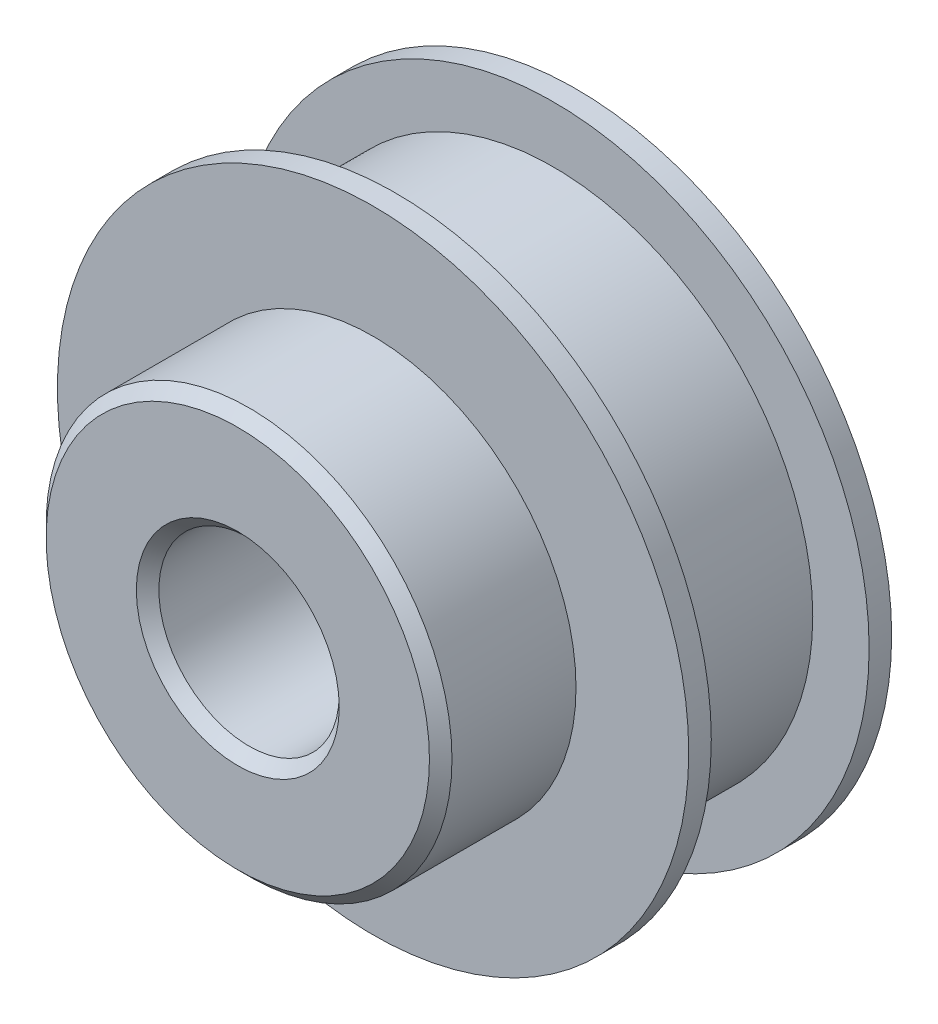
SolidWorks part; units mm, degrees
ref_plane "Front Plane" through (0, 0, 0) normal (0, 0, 1) x (1, 0, 0)
ref_plane "Top Plane" through (0, 0, 0) normal (0, 1, 0) x (1, 0, 0)
ref_plane "Right Plane" through (0, 0, 0) normal (1, 0, 0) x (0, 0, -1)
sketch "Sketch1" plane through (0, 0, 0) normal (0, 0, 1) x (1, 0, 0)
  circle A0 centre (0, 0) radius 14
  dimension "D1" = 28
extrude "Boss-Extrude1" add sketch "Sketch1" along normal blind 1
sketch "Sketch2" plane through (0, 0, 1) normal (0, 0, 1) x (1, 0, 0)
  circle A0 centre (0, 0) radius 11.5
  dimension "D1" = 23
extrude "Boss-Extrude2" add sketch "Sketch2" along normal blind 7
sketch "Sketch3" plane through (0, 0, 8) normal (0, 0, 1) x (1, 0, 0)
  circle A0 centre (0, 0) radius 14
extrude "Boss-Extrude3" add sketch "Sketch3" along normal blind 1
sketch "Sketch4" plane through (0, 0, 9) normal (0, 0, 1) x (1, 0, 0)
  circle A0 centre (0, 0) radius 9
  dimension "D1" = 18
extrude "Boss-Extrude4" add sketch "Sketch4" along normal blind 6
sketch "Sketch5" plane through (0, 0, 0) normal (0, 0, -1) x (-1, 0, 0)
  circle A0 centre (0, 0) radius 4
  dimension "D1" = 8
extrude "Cut-Extrude1" cut sketch "Sketch5" against normal blind 23
chamfer "Chamfer1" distance 0.5 angle 45 3 edges at (9, 0, 15) (4, 0, 15) (-4, 0, 0)
